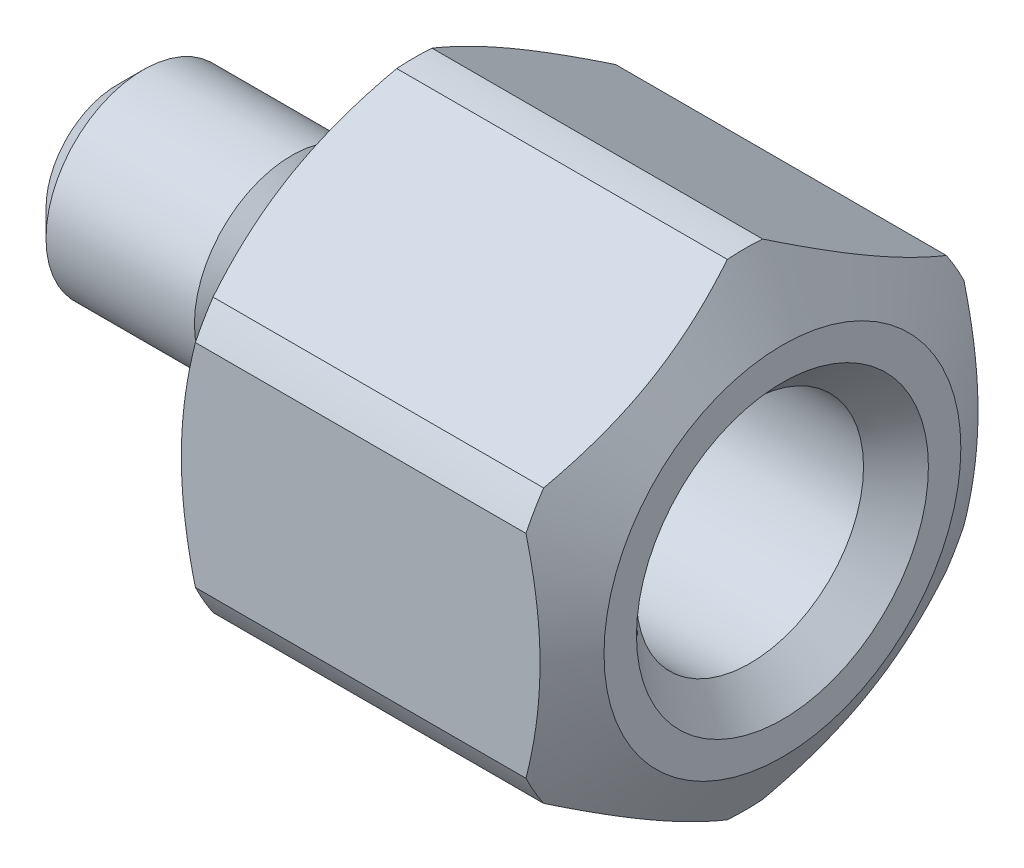
SolidWorks part; units mm, degrees
ref_plane "Спереди" through (0, 0, 0) normal (0, 0, 1) x (1, 0, 0)
ref_plane "Сверху" through (0, 0, 0) normal (0, 1, 0) x (1, 0, 0)
ref_plane "Справа" through (0, 0, 0) normal (1, 0, 0) x (0, 0, -1)
other "Configuration Table"
sketch "Эскиз1" plane through (0, 0, 0) normal (0, 0, 1) x (1, 0, 0)
  line L0 (0, 0) -> (50.3829, 0) construction
  line L1 (0, 2) -> (0, 4.4)
  line L2 (1.6, 6) -> (10.75, 6)
  line L3 (10.75, 6) -> (11.8536, 4.8964)
  line L4 (12.2071, 4.75) -> (15, 4.75)
  line L5 (16, 5.75) -> (16, 11)
  line L6 (16, 11) -> (18.3094, 15)
  line L7 (18.3094, 15) -> (38.6906, 15)
  line L8 (38.6906, 15) -> (41, 11)
  line L9 (41, 11) -> (41, 0)
  line L11 (33.5, 0) -> (25.1464, 8.3536)
  line L12 (24.7929, 8.5) -> (22, 8.5)
  line L13 (21, 7.5) -> (21, 4)
  line L14 (19, 2) -> (0, 2)
  line L15 (0, 4.4) -> (1.6, 6)
  line L16 (21, 4) -> (19, 2)
  line L20 (33.5, 0) -> (41, 0)
  arc A0 (22, 8.5) -> (21, 7.5) centre (22, 7.5) ccw
  arc A1 (15, 4.75) -> (16, 5.75) centre (15, 5.75) ccw
  arc A2 (25.1464, 8.3536) -> (24.7929, 8.5) centre (24.7929, 8) ccw
  arc A3 (11.8536, 4.8964) -> (12.2071, 4.75) centre (12.2071, 5.25) ccw
  point P4 (0, 6)
  point P10 (23.3964, 8.5)
  point P12 (41, 7)
  point P16 (21, 2)
  point P28 (21, 8.5)
  point P31 (16, 4.75)
  point P34 (25, 8.5)
  point P37 (12, 4.75)
  dimension "D20" = 1
  dimension "D21" = 0.5
  dimension "D1" = 12
  dimension "D2" = 4
  dimension "D3" = 9.5
  dimension "D4" = 17
  dimension "D6" = 22
  dimension "D7" = 30
  dimension "D8" = 30
  dimension "D9" = 30
  dimension "D10" = 45
  dimension "D11" = 4
  dimension "D12" = 4
  dimension "D13" = 1.6
  dimension "D15" = 16
  dimension "D16" = 45
  dimension "D17" = 2
  dimension "D18" = 45
revolve "Повернуть2" add sketch "Эскиз1" angle 360 about L0
cosmetic thread "Условное изображение резьбы1" parameters "D2"=10.072
sketch "Эскиз2" plane through (41, 0, 0) normal (1, 0, 0) x (0, 0, -1)
  line L1 (0, 15.5885) -> (-13.5, 7.7942)
  line L2 (-13.5, 7.7942) -> (-13.5, -7.7942)
  line L3 (-13.5, -7.7942) -> (0, -15.5885)
  line L4 (0, -15.5885) -> (13.5, -7.7942)
  line L5 (13.5, -7.7942) -> (13.5, 7.7942)
  line L6 (13.5, 7.7942) -> (0, 15.5885)
  circle A0 centre (0, 0) radius 13.5 construction
  dimension "D1" = 27
extrude "Вырез-Вытянуть1" cut sketch "Эскиз2" against normal through all flip side to cut
hole_wizard "Отверстие обработанное метчиком M161" positions "Эскиз3" profile "Эскиз4" tap size "M16" standard "IS"
sketch "Эскиз3" plane through (41, 0, 0) normal (1, 0, 0) x (0, 0, -1)
  point P0 (0, 0)
sketch "Эскиз4" plane through (41, 0, 0) normal (0, 1, 0) x (0, 0, -1)
  line L0 (0, 0) -> (0, 20)
  line L1 (0, 20) -> (7, 20)
  line L2 (7, 20) -> (7, 2)
  line L3 (7, 2) -> (9, 0)
  line L5 (9, 0) -> (0, 0)
  line L6 (-7, 2) -> (-9, 0) construction
  line L10 (0, 20) -> (-7, 20) construction
  line L11 (0, -6.35) -> (0, 107.95) construction
  dimension "Диаметр сверла" = 14
  dimension "Глубина сверла" = 20
  dimension "Диаметр передней зенковки" = 18
  dimension "Угол передней зенковки" = 90
  dimension "Угол заточки сверла" = 180
cosmetic thread "Отверстие резьбы1" parameters "D1"=32, "D2"=16
